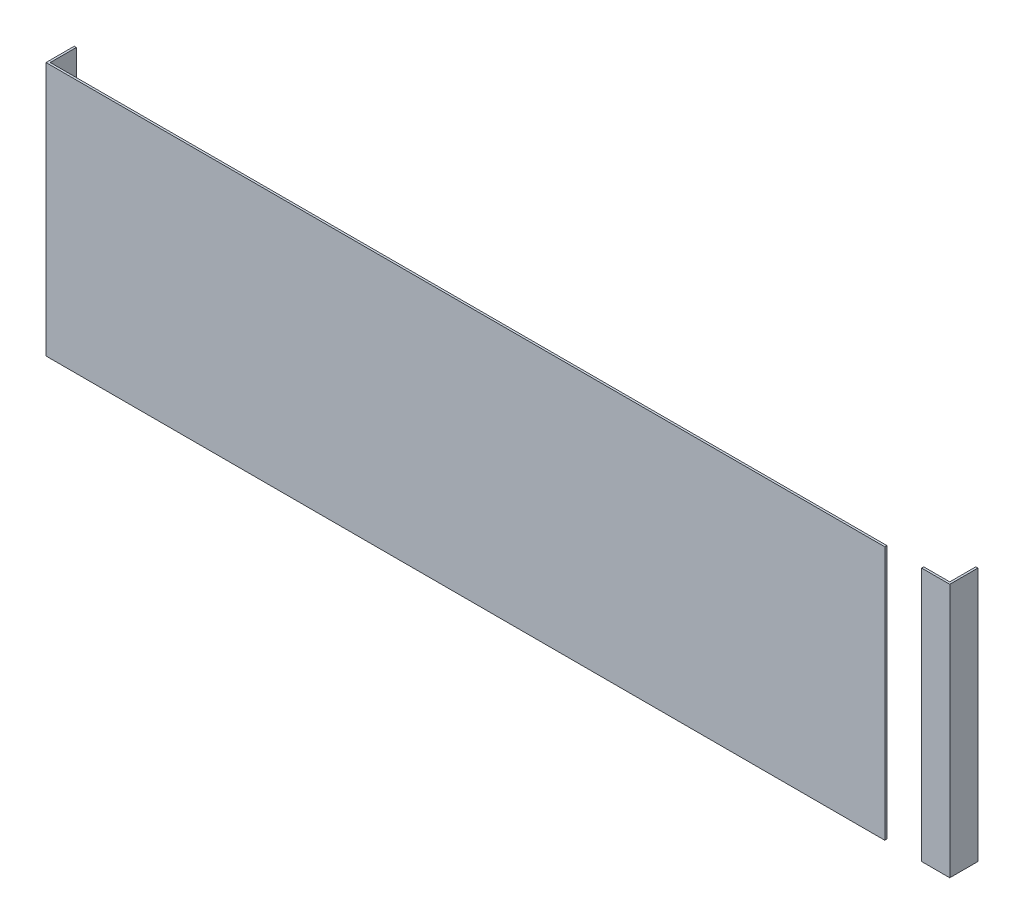
SolidWorks part; units mm, degrees
ref_plane "Front Plane" through (0, 0, 0) normal (0, 0, 1) x (1, 0, 0)
ref_plane "Top Plane" through (0, 0, 0) normal (0, 1, 0) x (1, 0, 0)
ref_plane "Right Plane" through (0, 0, 0) normal (1, 0, 0) x (0, 0, -1)
other "Configuration Table"
sketch "Sketch1" plane through (0, 0, 0) normal (0, 1, 0) x (1, 0, 0)
  line L0 (30, -40) -> (30, -20)
  line L1 (30, -20) -> (31.5, -20)
  line L2 (31.5, -20) -> (31.5, -38.5)
  line L3 (31.5, -38.5) -> (668.5, -38.5)
  line L4 (668.5, -38.5) -> (668.5, -20)
  line L5 (668.5, -20) -> (670, -20)
  line L6 (670, -20) -> (670, -40)
  line L7 (670, -40) -> (30, -40)
extrude "PACK_pano_kapagi_kapak_1" add sketch "Sketch1" along normal blind 180 from offset 120 separate body
sketch "Sketch2" plane through (0, 0, 0) normal (0, 0, 1) x (1, 0, 0)
  line L1 (624, 120) -> (650, 120)
  line L2 (624, 120) -> (624, 300)
  line L3 (624, 300) -> (650, 300)
  line L4 (650, 120) -> (650, 300)
extrude "PACK_pano_kapagi_kapak_2" cut sketch "Sketch2" along normal blind 14 from offset 27
